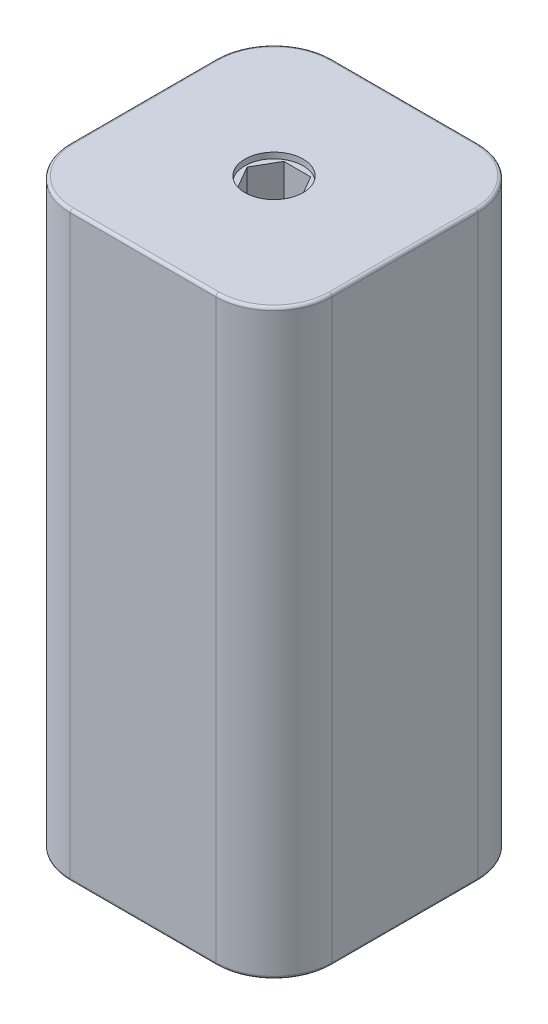
SolidWorks part; units mm, degrees
ref_plane "前视基准面" through (0, 0, 0) normal (0, 0, 1) x (1, 0, 0)
ref_plane "上视基准面" through (0, 0, 0) normal (0, 1, 0) x (1, 0, 0)
ref_plane "右视基准面" through (0, 0, 0) normal (1, 0, 0) x (0, 0, -1)
sketch "草图1" plane through (0, 0, 0) normal (0, 1, 0) x (1, 0, 0)
  line L1 (-22.5, -22.5) -> (22.5, -22.5)
  line L2 (-22.5, -22.5) -> (-22.5, 22.5)
  line L3 (-22.5, 22.5) -> (22.5, 22.5)
  line L4 (22.5, -22.5) -> (22.5, 22.5)
  line L5 (-22.5, -22.5) -> (22.5, 22.5) construction
  line L6 (-22.5, 22.5) -> (22.5, -22.5) construction
  point P0 (0, 0)
  dimension "D1" = 45
  dimension "D2" = 45
extrude "凸台-拉伸1" add sketch "草图1" against normal blind 100
fillet "圆角1" radius 10 4 edges at (-22.5, -50, -22.5) (22.5, -50, -22.5) (22.5, -50, 22.5) (-22.5, -50, 22.5)
fillet "圆角2" radius 0.5 16 edges at (19.5711, 0, -19.5711) (22.5, 0, 0) (19.5711, 0, 19.5711) (0, 0, 22.5) (-19.5711, 0, 19.5711) (-22.5, 0, 0) (-19.5711, 0, -19.5711) (0, 0, -22.5) (-19.5711, -100, 19.5711) (0, -100, 22.5) (19.5711, -100, 19.5711) (22.5, -100, 0) (19.5711, -100, -19.5711) (0, -100, -22.5) (-19.5711, -100, -19.5711) (-22.5, -100, 0)
sketch "草图2" plane through (0, 0, 0) normal (0, 1, 0) x (1, 0, 0)
  circle A0 centre (0, 0) radius 5
  dimension "D1" = 10
extrude "切除-拉伸1" cut sketch "草图2" against normal blind 1
sketch "草图3" plane through (0, -1, 0) normal (0, 1, 0) x (1, 0, 0)
  line L1 (4.6188, 0) -> (2.3094, 4)
  line L2 (2.3094, 4) -> (-2.3094, 4)
  line L3 (-2.3094, 4) -> (-4.6188, 0)
  line L4 (-4.6188, 0) -> (-2.3094, -4)
  line L5 (-2.3094, -4) -> (2.3094, -4)
  line L6 (2.3094, -4) -> (4.6188, 0)
  circle A0 centre (0, 0) radius 4 construction
  dimension "D1" = 8
extrude "切除-拉伸2" cut sketch "草图3" against normal blind 12
